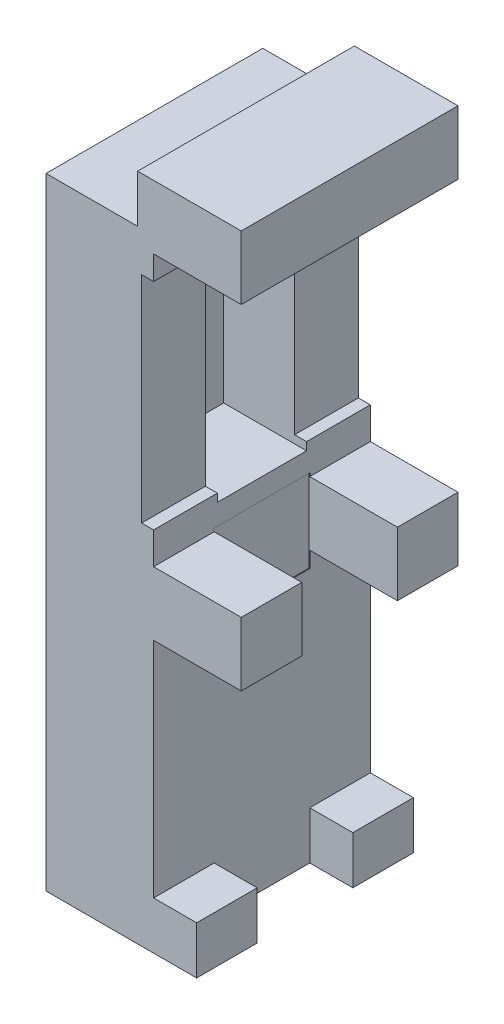
SolidWorks part; units mm, degrees
ref_plane "前视基准面" through (0, 0, 0) normal (0, 0, 1) x (1, 0, 0)
ref_plane "上视基准面" through (0, 0, 0) normal (0, 1, 0) x (1, 0, 0)
ref_plane "右视基准面" through (0, 0, 0) normal (1, 0, 0) x (0, 0, -1)
other "Configuration Table"
sketch "草图1" plane through (0, 0, 0) normal (0, 0, 1) x (1, 0, 0)
  line L0 (-10.2, 0) -> (-16.95, 0)
  line L1 (-16.95, 0) -> (-16.95, 54)
  line L2 (-16.95, 54) -> (-11.2, 54)
  line L3 (-11.2, 54) -> (-11.2, 57)
  line L4 (-11.2, 57) -> (-4.7, 57)
  line L5 (-4.7, 57) -> (-4.7, 53)
  line L6 (-4.7, 53) -> (-10.2, 53)
  line L7 (-10.2, 53) -> (-10.2, 51.5)
  line L8 (-10.2, 51.5) -> (-10.95, 51.5)
  line L9 (-10.95, 51.5) -> (-10.95, 38)
  line L10 (-10.95, 38) -> (-10.2, 38)
  line L11 (-10.2, 38) -> (-10.2, 36)
  line L12 (-10.2, 36) -> (-4.7, 36)
  line L13 (-4.7, 36) -> (-4.7, 32)
  line L14 (-4.7, 32) -> (-10.2, 32)
  line L15 (-10.2, 32) -> (-10.2, 0)
  dimension "x0" = 10.2
  dimension "x1" = 16.95
  dimension "x3" = 11.2
  dimension "x5" = 4.7
  dimension "x7" = 10.2
  dimension "x9" = 10.95
  dimension "x11" = 10.2
  dimension "x13" = 4.7
  dimension "y2" = 54
  dimension "y4" = 57
  dimension "y6" = 53
  dimension "y8" = 51.5
  dimension "y10" = 38
  dimension "y12" = 36
  dimension "y14" = 32
extrude "Guide_and_solid_stops" add sketch "草图1" along normal blind 13.6
ref_plane "Channel_midplane" through (0, 0, 6.8) normal (0, 0, 1) x (1, 0, 0)
sketch "草图3" plane through (0, 0, 6.8) normal (0, 0, 1) x (1, 0, 0)
  line L0 (-7, 37.5) -> (-15.4, 37.5)
  line L1 (-15.4, 37.5) -> (-15.4, 51.5)
  line L2 (-15.4, 51.5) -> (-7, 51.5)
  line L3 (-7, 51.5) -> (-7, 37.5)
  dimension "x0" = 7
  dimension "x1" = 15.4
  dimension "y0" = 37.5
  dimension "y2" = 51.5
extrude "Nut_tongue_channel" cut sketch "草图3" against normal mid plane 5.6
sketch "草图4" plane through (0, 0, 6.8) normal (0, 0, 1) x (1, 0, 0)
  line L0 (-4, 31) -> (-10.25, 31)
  line L1 (-10.25, 31) -> (-10.25, 36.2)
  line L2 (-10.25, 36.2) -> (-4, 36.2)
  line L3 (-4, 36.2) -> (-4, 31)
  dimension "x0" = 4
  dimension "x1" = 10.25
  dimension "y0" = 31
  dimension "y2" = 36.2
extrude "Lower_yoke_relief" cut sketch "草图4" against normal mid plane 6
sketch "草图5" plane through (0, 0, 0) normal (0, 0, 1) x (1, 0, 0)
  line L0 (-7.5, 15) -> (-11.2, 15)
  line L1 (-11.2, 15) -> (-11.2, 18)
  line L2 (-11.2, 18) -> (-7.5, 18)
  line L3 (-7.5, 18) -> (-7.5, 15)
  dimension "x0" = 7.5
  dimension "x1" = 11.2
  dimension "y0" = 15
  dimension "y2" = 18
extrude "Lower_inward_stop" add sketch "草图5" along normal blind 3.8
ref_plane "Lower_stop_rear_plane" through (0, 0, 9.8) normal (0, 0, 1) x (1, 0, 0)
sketch "草图7" plane through (0, 0, 9.8) normal (0, 0, 1) x (1, 0, 0)
  line L0 (-7.5, 15) -> (-11.2, 15)
  line L1 (-11.2, 15) -> (-11.2, 18)
  line L2 (-11.2, 18) -> (-7.5, 18)
  line L3 (-7.5, 18) -> (-7.5, 15)
  dimension "x0" = 7.5
  dimension "x1" = 11.2
  dimension "y0" = 15
  dimension "y2" = 18
extrude "凸台-拉伸2" add sketch "草图7" along normal blind 3.8
sketch "草图8" plane through (0, 0, 0) normal (0, 0, 1) x (1, 0, 0)
  line L0 (-3, -2) -> (-20, -2)
  line L1 (-20, -2) -> (-20, 15)
  line L2 (-20, 15) -> (-3, 15)
  line L3 (-3, 15) -> (-3, -2)
  dimension "x0" = 3
  dimension "x1" = 20
  dimension "y0" = 2
  dimension "y2" = 15
extrude "Remove_lower_tail" cut sketch "草图8" against normal through all and the other way through all
